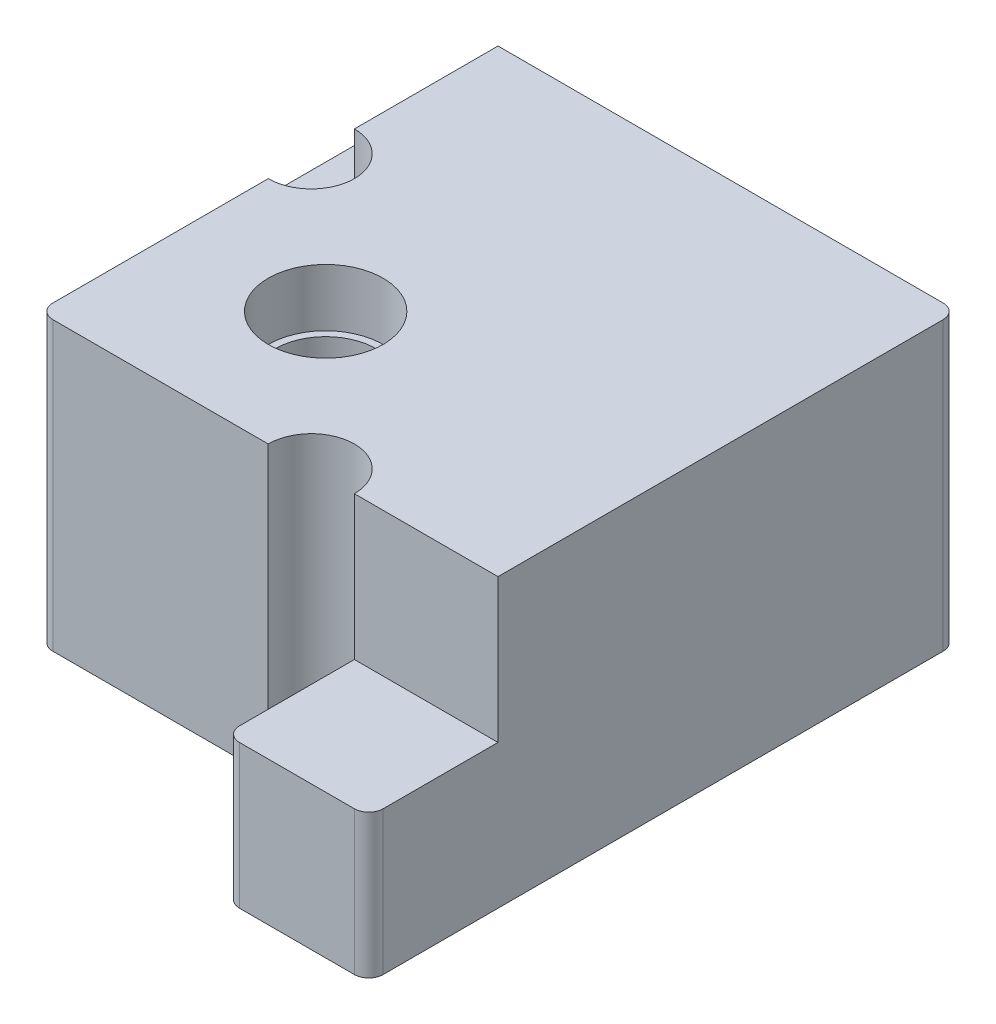
SolidWorks part; units mm, degrees
ref_plane "Front Plane" through (0, 0, 0) normal (0, 0, 1) x (1, 0, 0)
ref_plane "Top Plane" through (0, 0, 0) normal (0, 1, 0) x (1, 0, 0)
ref_plane "Right Plane" through (0, 0, 0) normal (1, 0, 0) x (0, 0, -1)
sketch "Sketch1" plane through (0, 0, 0) normal (0, 1, 0) x (1, 0, 0)
  line L1 (0, 0) -> (20.5, 0)
  line L2 (4.5, -5) -> (4.5, -16)
  line L3 (4.5, -16) -> (15.5, -16)
  line L6 (20.5, 0) -> (20.5, -20.5)
  line L7 (20.5, -20.5) -> (15.5, -20.5)
  line L8 (15.5, -16) -> (15.5, -20.5)
  line L9 (4.5, -5) -> (0, -5)
  line L10 (0, 0) -> (0, -5)
  dimension "D1" = 16
  dimension "D2" = 16
  dimension "D3" = 4.5
  dimension "D4" = 5
  dimension "D5" = 5
  dimension "D6" = 4.5
extrude "Boss-Extrude1" add sketch "Sketch1" along normal blind 10
sketch "Sketch4" plane through (0, 10, 0) normal (0, 1, 0) x (1, 0, 0)
  line L0 (4.5, -5) -> (4.5, -16) construction
  line L2 (4.5, -16) -> (15.5, -16) construction
  circle A0 centre (9.5, -11) radius 1.75
  dimension "D3" = 3.5
  dimension "D1" = 5
  dimension "D2" = 5
extrude "Cut-Extrude3" cut sketch "Sketch4" against normal blind 10
sketch "Sketch6" plane through (0, 10, 0) normal (0, 1, 0) x (1, 0, 0)
  circle A0 centre (9.5, -11) radius 2
  dimension "D1" = 4
extrude "Cut-Extrude5" cut sketch "Sketch6" against normal blind 2
sketch "Sketch7" plane through (0, 0, 0) normal (0, -1, 0) x (1, 0, 0)
  line L0 (0, 6.5) -> (4.5, 6.5) construction
  line L1 (4.5, 5) -> (4.5, 16) construction
  line L2 (0, 8) -> (4.5, 8)
  line L3 (0, 5) -> (4.5, 5)
  line L4 (0, 5) -> (4.5, 5) construction
  line L5 (0, 0) -> (0, 5) construction
  line L6 (14, 16) -> (14, 20.5) construction
  line L7 (4.5, 16) -> (15.5, 16) construction
  line L8 (12.5, 16) -> (12.5, 20.5)
  line L9 (15.5, 16) -> (15.5, 20.5)
  line L10 (15.5, 20.5) -> (20.5, 20.5) construction
  line L11 (15.5, 16) -> (15.5, 20.5) construction
  arc A0 (0, 8) -> (0, 5) centre (0, 6.5) ccw
  arc A1 (4.5, 5) -> (4.5, 8) centre (4.5, 6.5) ccw
  arc A2 (12.5, 16) -> (15.5, 16) centre (14, 16) ccw
  arc A3 (15.5, 20.5) -> (12.5, 20.5) centre (14, 20.5) ccw
  point P4 (2.25, 6.5)
  point P17 (14, 18.25)
  dimension "D1" = 3
  dimension "D2" = 3
extrude "Cut-Extrude6" cut sketch "Sketch7" against normal through all
sketch "Sketch8" plane through (0, 10, 0) normal (0, 1, 0) x (1, 0, 0)
  line L0 (20.5, -20.5) -> (20.5, 0) construction
  line L1 (15.5, -16) -> (20.5, -16)
  line L2 (15.5, -16) -> (15.5, -20.5)
  line L3 (15.5, -20.5) -> (20.5, -20.5)
  line L4 (20.5, -16) -> (20.5, -20.5)
  line L5 (4.5, -5) -> (0, -5)
  line L6 (4.5, -5) -> (4.5, 0)
  line L7 (4.5, 0) -> (0, 0)
  line L8 (0, -5) -> (0, 0)
  line L9 (15.5, -20.5) -> (20.5, -20.5) construction
  line L10 (0, -5) -> (4.5, -5) construction
  line L11 (4.5, -8) -> (4.5, -16) construction
  line L12 (4.5, -16) -> (12.5, -16) construction
  line L13 (15.5, -16) -> (15.5, -20.5) construction
extrude "Cut-Extrude7" cut sketch "Sketch8" against normal blind 5
fillet "Fillet1" radius 0.5 6 edges at (20.5, 5, 0) (0, 2.5, 0) (0, 2.5, 5) (4.5, 5, 16) (15.5, 2.5, 20.5) (20.5, 2.5, 20.5)
